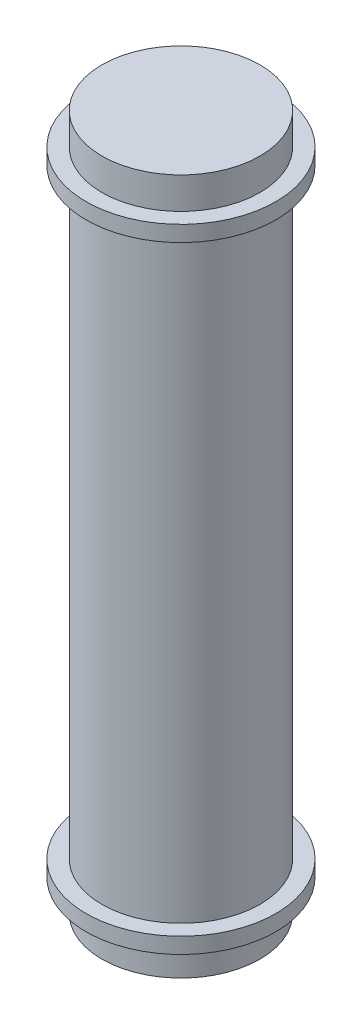
SolidWorks part; units mm, degrees
ref_plane "Alzado" through (0, 0, 0) normal (0, 0, 1) x (1, 0, 0)
ref_plane "Planta" through (0, 0, 0) normal (0, 1, 0) x (1, 0, 0)
ref_plane "Vista lateral" through (0, 0, 0) normal (1, 0, 0) x (0, 0, -1)
sketch "Croquis1" plane through (0, 0, 0) normal (0, 1, 0) x (1, 0, 0)
  circle A0 centre (0, 0) radius 0.5
  dimension "D1" = 1
extrude "Saliente-Extruir1" add sketch "Croquis1" along normal blind 4.4
sketch "Croquis2" plane through (0, 0, 0) normal (0, -1, 0) x (1, 0, 0)
  circle A2 centre (0, 0) radius 0.6
  circle A3 centre (0, 0) radius 0.6
  dimension "D1" = 0.1
extrude "Saliente-Extruir2" add sketch "Croquis2" against normal blind 0.1 from offset 0.2 offset against normal yes
ref_plane "Plano1" through (0, 2.2, 0) normal (0, -1, 0) x (-1, 0, 0)
mirror "Simetría1" about plane through (0, 2.2, 0) normal (0, -1, 0) of "Saliente-Extruir2"
equation "\"Ancho\"= 4.4mm"
equation "\"D1@Saliente-Extruir1\"=\"Ancho\""
